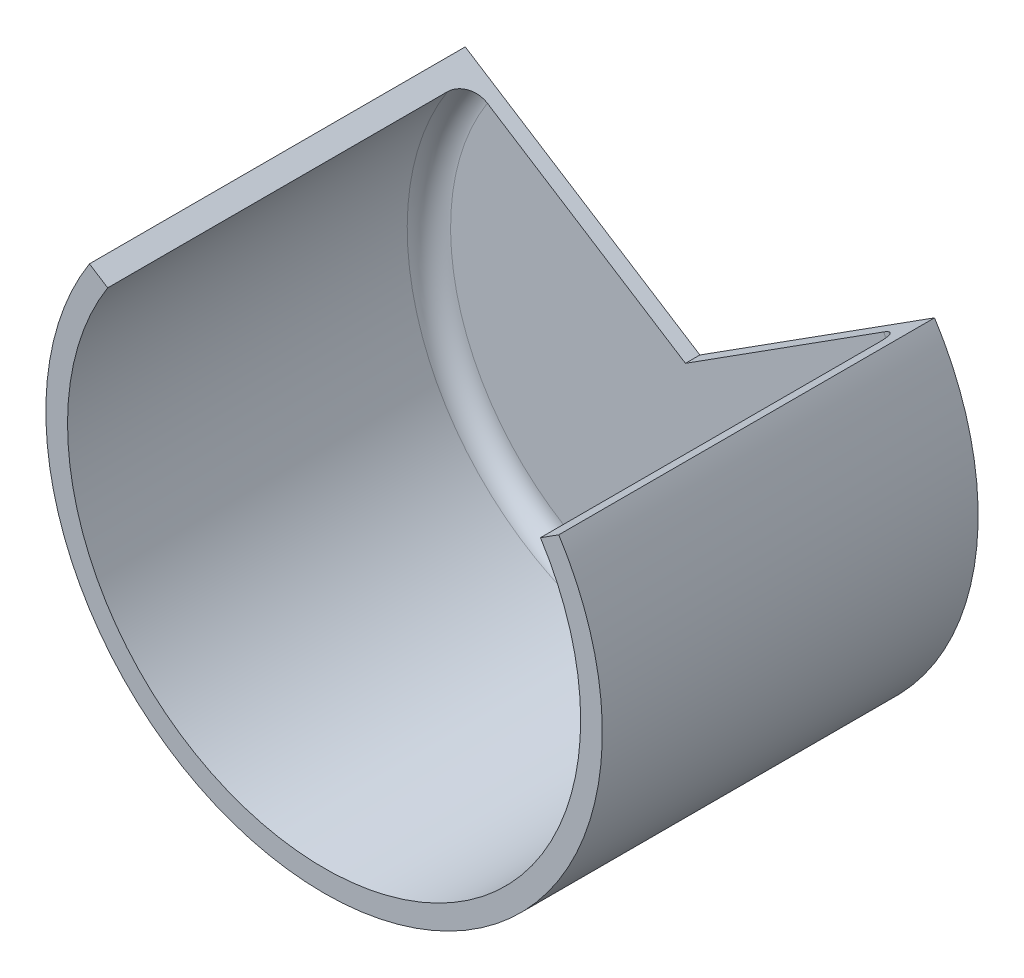
SolidWorks part; units mm, degrees
ref_plane "Front" through (0, 0, 0) normal (0, 0, 1) x (1, 0, 0)
ref_plane "Top" through (0, 0, 0) normal (0, 1, 0) x (1, 0, 0)
ref_plane "Right" through (0, 0, 0) normal (1, 0, 0) x (0, 0, -1)
sketch "Sketch1" plane through (0, 0, 0) normal (0, 0, 1) x (1, 0, 0)
  circle A0 centre (0, 0) radius 17.75
  circle A1 centre (0, 0) radius 19.25
  dimension "D1" = 35.5
  dimension "D2" = 1.5
extrude "Boss-Extrude1" add sketch "Sketch1" along normal blind 25
sketch "Sketch2" plane through (0, 0, 0) normal (0, 0, -1) x (-1, 0, 0)
  circle A1 centre (0, 0) radius 19.25
  circle A2 centre (0, 0) radius 19.25
  dimension "D1" = 0
extrude "Boss-Extrude2" add sketch "Sketch2" along normal blind 1
sketch "Sketch3" plane through (0, 0, -1) normal (0, 0, -1) x (-1, 0, 0)
  line L0 (-16.2353, 10.343) -> (0, 0)
  line L1 (0, 0) -> (16.2353, 10.343)
  line L2 (0, 0) -> (0, 19.25) construction
  circle A0 centre (0, 0) radius 19.25 construction
  arc A1 (-16.2353, 10.343) -> (16.2353, 10.343) centre (0, 0) cw
  dimension "D1" = 115
extrude "Cut-Extrude1" cut sketch "Sketch3" against normal through all
fillet "Fillet2" radius 1.5 1 edges at (0, -17.75, 0)
